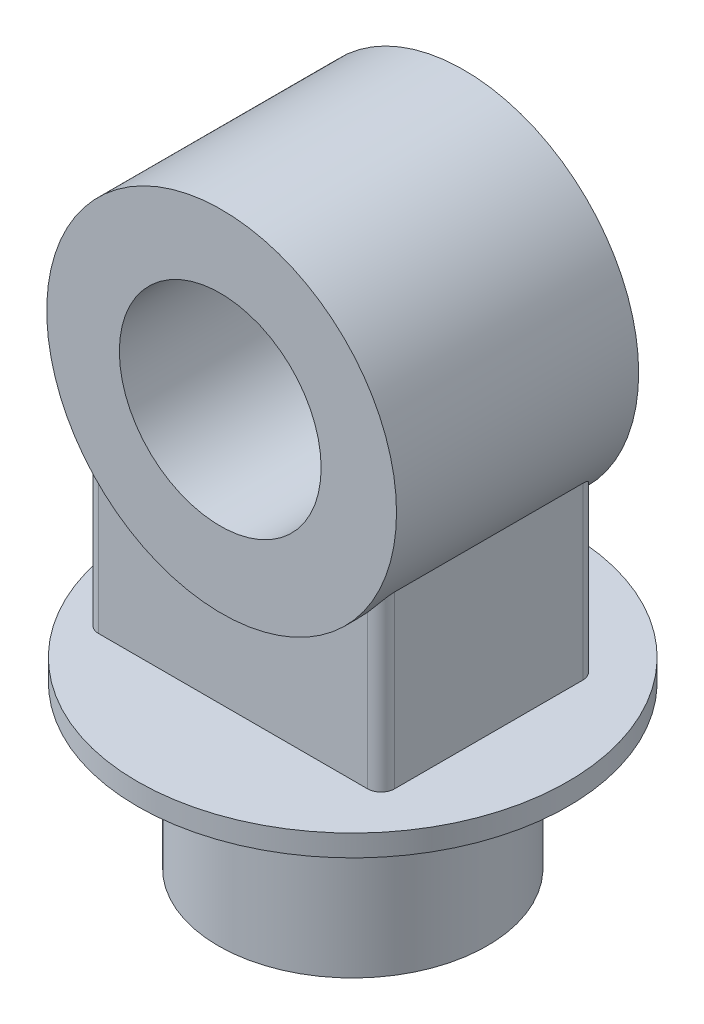
SolidWorks part; units mm, degrees
ref_plane "Front Plane" through (0, 0, 0) normal (0, 0, 1) x (1, 0, 0)
ref_plane "Top Plane" through (0, 0, 0) normal (0, 1, 0) x (1, 0, 0)
ref_plane "Right Plane" through (0, 0, 0) normal (1, 0, 0) x (0, 0, -1)
sketch "Sketch2" plane through (0, 0, 0) normal (0, 1, 0) x (1, 0, 0)
  circle A1 centre (0.2617, 0.0362) radius 100
  dimension "D1" = 200
extrude "Boss-Extrude1" add sketch "Sketch2" along normal blind 120
sketch "Sketch3" plane through (0, 120, 0) normal (0, 1, 0) x (1, 0, 0)
  circle A0 centre (0.5279, -0.23) radius 160
  dimension "D1" = 320
extrude "Boss-Extrude2" add sketch "Sketch3" along normal blind 16
sketch "Sketch5" plane through (0, 0, 0) normal (0, 0, 1) x (1, 0, 0)
  line L0 (160.5279, 136) -> (-159.4721, 136) construction
  circle A0 centre (-8.1942, 336) radius 75
  circle A1 centre (-7.1626, 335.2298) radius 130
  dimension "D1" = 150
  dimension "D2" = 260
  dimension "D3" = 200
extrude "Boss-Extrude3" add sketch "Sketch5" along normal mid plane 180 separate body
sketch "Sketch6" plane through (0, 136, 0) normal (0, 1, 0) x (1, 0, 0)
  line L1 (100.7325, -79.3782) -> (-119.2675, -79.3782)
  line L2 (100.7325, -79.3782) -> (100.7325, 80.6218)
  line L3 (100.7325, 80.6218) -> (-119.2675, 80.6218)
  line L4 (-119.2675, -79.3782) -> (-119.2675, 80.6218)
  line L5 (-9.2675, 80.6218) -> (-9.2675, -79.3782) construction
  line L6 (100.7325, 0.6218) -> (-119.2675, 0.6218) construction
  point P0 (-9.2675, 0.6218)
  dimension "D1" = 160
  dimension "D2" = 220
extrude "Boss-Extrude4" add sketch "Sketch6" along normal up to next
fillet "Fillet1" radius 10 4 edges at (-119.2675, 202.7041, 79.3782) (-119.2675, 202.7041, -80.6218) (100.7325, 199.3566, -80.6218) (100.7325, 199.3566, 79.3782)
